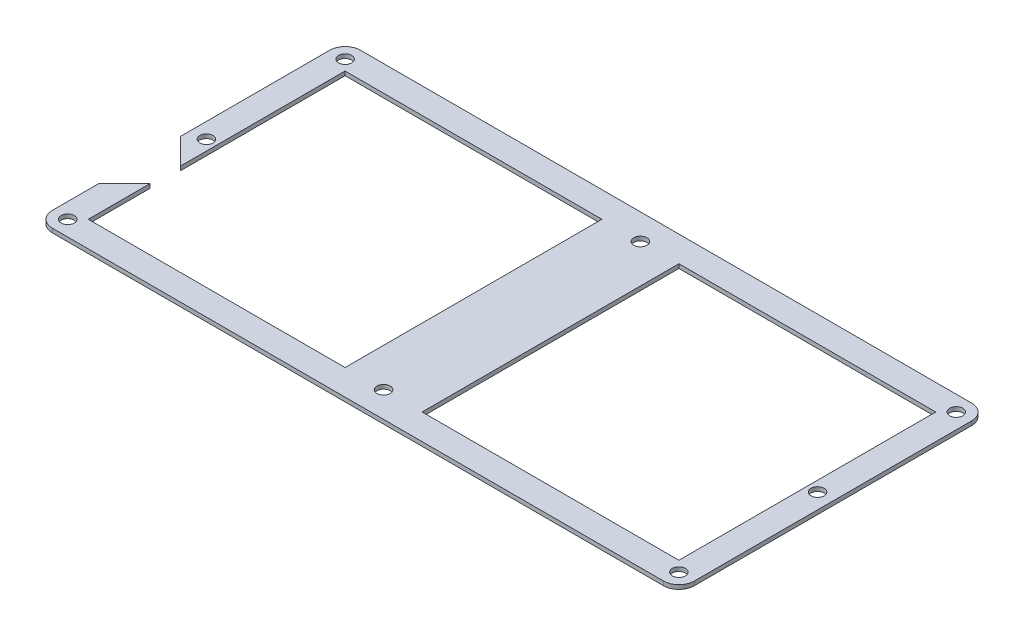
SolidWorks part; units mm, degrees
ref_plane "前视基准面" through (0, 0, 0) normal (0, 0, 1) x (1, 0, 0)
ref_plane "上视基准面" through (0, 0, 0) normal (0, 1, 0) x (1, 0, 0)
ref_plane "右视基准面" through (0, 0, 0) normal (1, 0, 0) x (0, 0, -1)
sketch "草图1" plane through (0, 0, 0) normal (0, 1, 0) x (1, 0, 0)
  line L0 (13.4957, 64.6198) -> (13.4957, 122.6198)
  line L1 (19.4957, 128.6198) -> (257.4957, 128.6198)
  line L2 (263.4957, 122.6198) -> (263.4957, 14.6198)
  line L3 (257.4957, 8.6198) -> (19.4957, 8.6198)
  line L4 (13.4957, 14.6198) -> (13.4957, 32.6198)
  line L5 (23.4957, 54.6198) -> (23.4957, 118.6198)
  line L6 (23.4957, 118.6198) -> (123.4957, 118.6198)
  line L7 (123.4957, 118.6198) -> (123.4957, 18.6198)
  line L8 (123.4957, 18.6198) -> (23.4957, 18.6198)
  line L9 (23.4957, 18.6198) -> (23.4957, 42.6198)
  line L10 (253.4957, 118.6198) -> (153.4957, 118.6198)
  line L11 (153.4957, 118.6198) -> (153.4957, 18.6198)
  line L12 (153.4957, 18.6198) -> (253.4957, 18.6198)
  line L13 (253.4957, 18.6198) -> (253.4957, 118.6198)
  line L14 (23.4957, 54.6198) -> (13.4957, 64.6198)
  line L15 (23.4957, 42.6198) -> (13.4957, 32.6198)
  arc A0 (19.4957, 128.6198) -> (13.4957, 122.6198) centre (19.4957, 122.6198) ccw
  arc A1 (263.4957, 122.6198) -> (257.4957, 128.6198) centre (257.4957, 122.6198) ccw
  arc A2 (257.4957, 8.6198) -> (263.4957, 14.6198) centre (257.4957, 14.6198) ccw
  arc A3 (13.4957, 14.6198) -> (19.4957, 8.6198) centre (19.4957, 14.6198) ccw
  circle A4 centre (19.4957, 122.6198) radius 2.55
  circle A5 centre (257.4957, 122.6198) radius 2.55
  circle A6 centre (138.4957, 118.6198) radius 2.55
  circle A7 centre (19.4957, 14.6198) radius 2.55
  circle A8 centre (257.4957, 14.6198) radius 2.55
  circle A9 centre (138.4957, 18.6198) radius 2.55
  circle A10 centre (257.4957, 68.6198) radius 2.55
  circle A11 centre (19.4957, 68.6198) radius 2.55
extrude "凸台-拉伸1" add sketch "草图1" along normal blind 1.6
